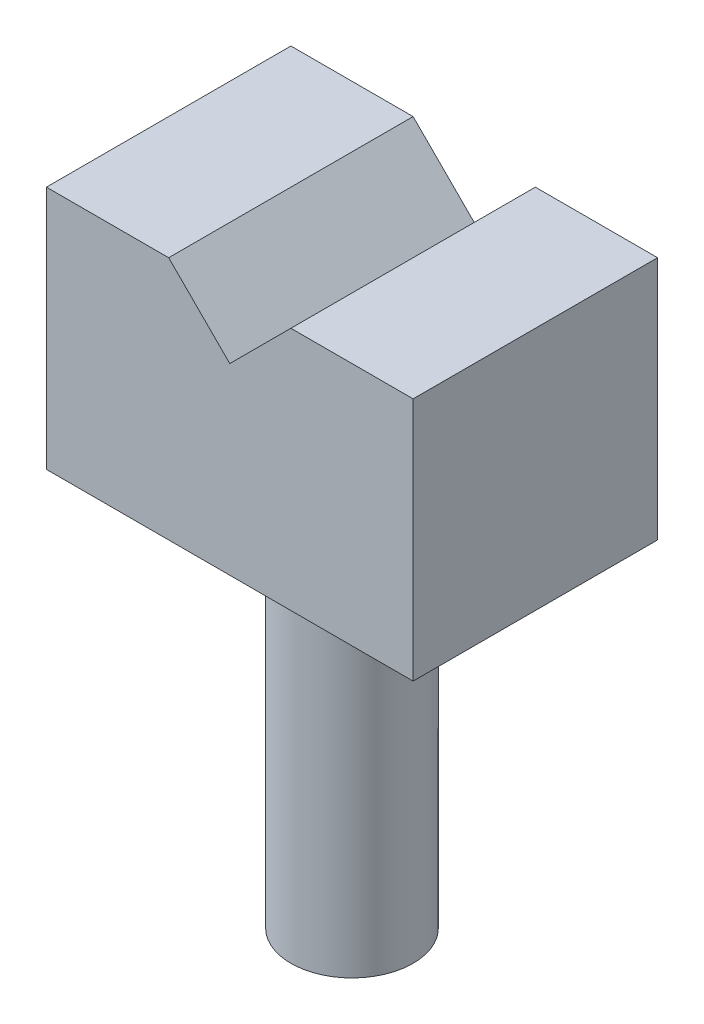
SolidWorks part; units mm, degrees
ref_plane "Ön Düzlem" through (0, 0, 0) normal (0, 0, 1) x (1, 0, 0)
ref_plane "Üst Düzlem" through (0, 0, 0) normal (0, 1, 0) x (1, 0, 0)
ref_plane "Sağ Düzlem" through (0, 0, 0) normal (1, 0, 0) x (0, 0, -1)
sketch "Çizim1" plane through (0, 0, 0) normal (0, 0, 1) x (1, 0, 0)
  line L0 (0, 0) -> (0, 20)
  line L1 (0, 20) -> (10, 20)
  line L3 (10, 20) -> (15, 15)
  line L6 (10, 20) -> (20, 20)
  line L7 (20, 20) -> (15, 15)
  line L8 (20, 20) -> (30, 20)
  line L9 (30, 20) -> (30, 0)
  line L10 (30, 0) -> (0, 0)
extrude "Yükseklik-Ekstrüzyon1" add sketch "Çizim1" along normal blind 20 contours L10 L9 L8 L7 L3 L1 L0
sketch "Çizim2" plane through (0, 0, 0) normal (0, -1, 0) x (1, 0, 0)
  circle A0 centre (15, 10) radius 5
extrude "Yükseklik-Ekstrüzyon2" add sketch "Çizim2" along normal blind 30
